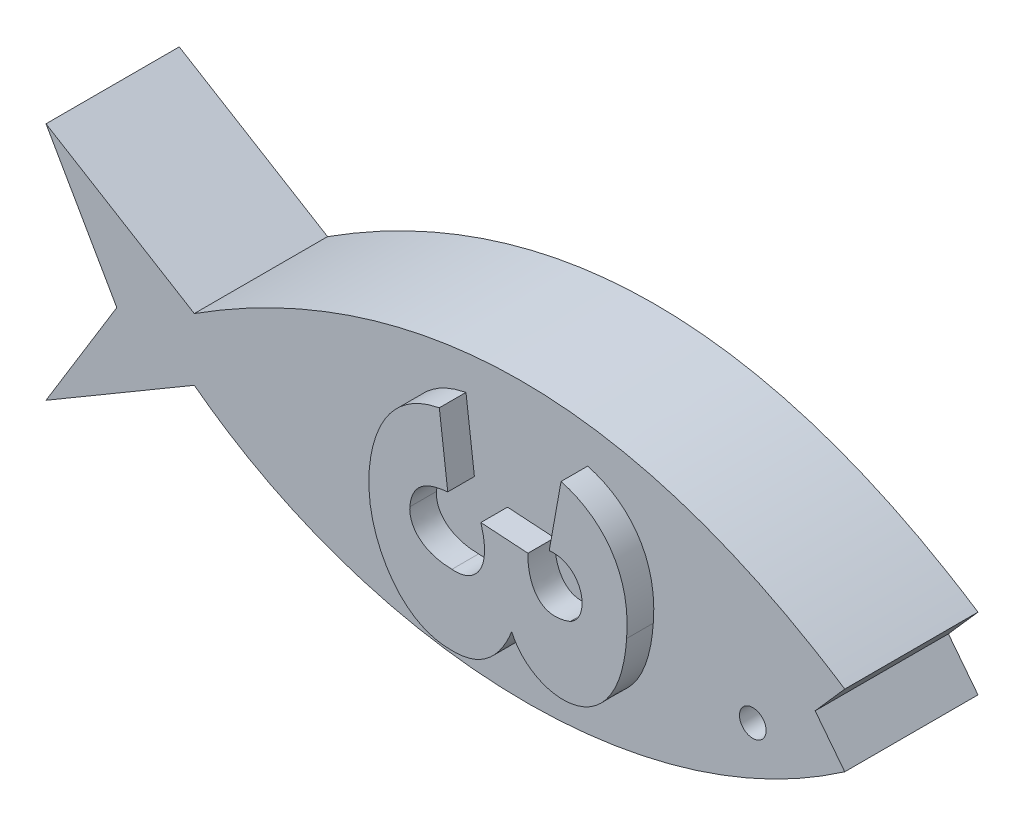
SolidWorks part; units mm, degrees
ref_plane "Front" through (0, 0, 0) normal (0, 0, 1) x (1, 0, 0)
ref_plane "Top" through (0, 0, 0) normal (0, 1, 0) x (1, 0, 0)
ref_plane "Right" through (0, 0, 0) normal (1, 0, 0) x (0, 0, -1)
sketch "Sketch2" plane through (0, 0, 0) normal (0, 0, -1) x (1, 0, 0)
  line L0 (29.973, 6.6427) -> (28.8624, 5.2157)
  line L1 (28.8624, 5.2157) -> (29.973, 3.9538)
  line L2 (5.5653, 6.2857) -> (0, 9.5561)
  line L3 (0, 9.5561) -> (2.6565, 5.2157)
  line L4 (2.6565, 5.2157) -> (0, 0.5701)
  line L5 (0, 0.5701) -> (5.5653, 3.9538)
  circle A0 centre (26.5226, 6.7807) radius 0.5001
  spline S0 degree 3 poles (5.5653, 6.2857) (12.0373, 11.2173) (22.1418, 12.0787) (29.973, 6.6427) knots 0 0 0 0 1 1 1 1
  spline S1 degree 2 poles (5.5653, 3.9538) (17.9191, -3.9397) (29.973, 3.9538) knots 0 0 0 1 1 1
extrude "Boss-Extrude1" add sketch "Sketch2" against normal blind 5
ref_plane "Fish Top Plane" through (0, 0, 5) normal (0, 0, 1) x (-1, 0, 0)
sketch "Sketch6" plane through (0, 0, 5) normal (0, 0, 1) x (-1, 0, 0)
  line L0 (-15.7594, 1.419) -> (-16.0758, 3.995)
  line L1 (-20.3275, 1.5298) -> (-19.8843, 3.995)
  line L2 (-17.3177, 4.3691) -> (-19.0854, 4.4826)
  line L3 (8.1953, 12.0475) -> (8.1953, -4.362) construction
  line L4 (8.1953, -4.362) -> (29.5196, -4.362) construction
  spline S0 degree 3 poles (-15.7594, 1.419) (-13.3214, 1.8894) (-13.0535, 4.4287) (-13.1237, 5.4049) knots 0 0 0 0 1 1 1 1
  spline S1 degree 3 poles (-13.1237, 5.4049) (-13.1736, 6.9719) (-14.2444, 9.0173) (-16.0758, 9.0664) knots 0 0 0 0 1 1 1 1
  spline S2 degree 2 poles (-16.0758, 9.0664) (-17.7334, 9.1935) (-18.4749, 7.3381) knots 0 0 0 1 1 1
  spline S3 degree 3 poles (-18.4749, 7.3381) (-19.2493, 9.1018) (-22.5093, 9.4293) (-22.7877, 5.4049) knots 0 0 0 0 1 1 1 1
  spline S4 degree 3 poles (-22.7877, 5.4049) (-22.9638, 3.3371) (-21.9498, 1.978) (-20.3275, 1.5298) knots 0 0 0 0 1 1 1 1
  spline S5 degree 3 poles (-19.0854, 4.4826) (-19.0561, 4.9972) (-19.2582, 6.439) (-20.6694, 5.9114) knots 0 0 0 0 1 1 1 1
  spline S6 degree 3 poles (-20.6694, 5.9114) (-21.4863, 5.4579) (-21.1623, 3.8833) (-19.8843, 3.995) knots 0 0 0 0 1 1 1 1
  spline S7 degree 3 poles (-16.0758, 3.995) (-15.4589, 4.0627) (-14.7409, 4.2384) (-14.6504, 5.193) knots 0 0 0 0 1 1 1 1
  spline S8 degree 3 poles (-14.6504, 5.193) (-14.6192, 5.8621) (-15.1698, 6.415) (-16.2321, 6.4324) knots 0 0 0 0 1 1 1 1
  spline S9 degree 3 poles (-16.2321, 6.4324) (-17.0052, 6.5118) (-17.7801, 5.8699) (-17.3177, 4.3691) knots 0 0 0 0 1 1 1 1
extrude "Boss-Extrude2" add sketch "Sketch6" along normal blind 1
